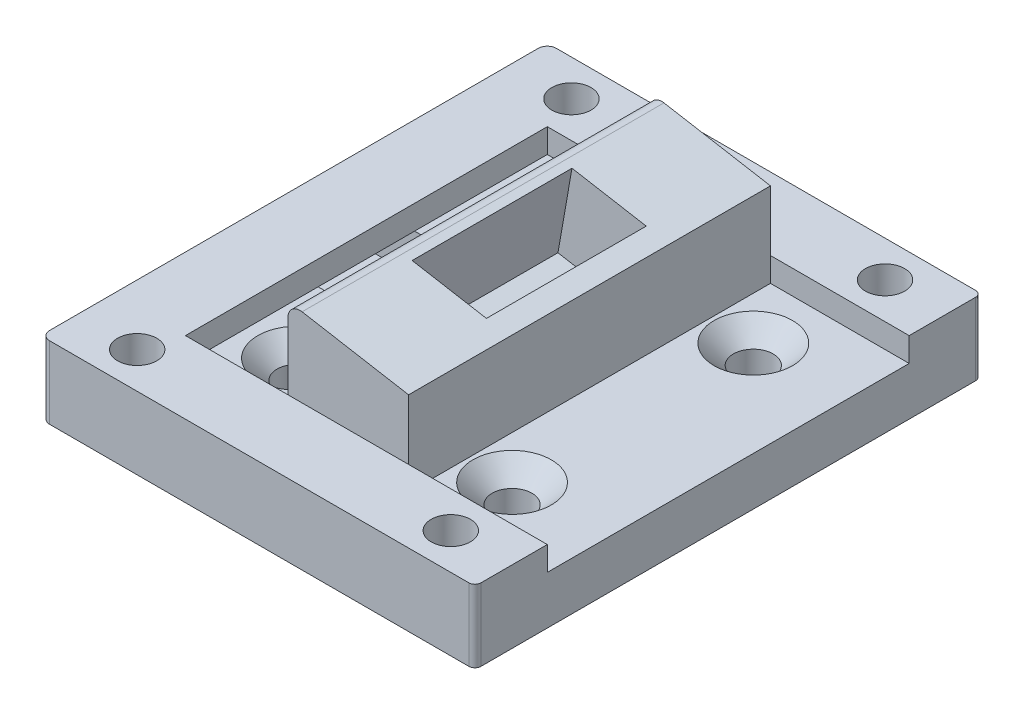
SolidWorks part; units mm, degrees
ref_plane "Ebene vorne" through (0, 0, 0) normal (0, 0, 1) x (1, 0, 0)
ref_plane "Ebene oben" through (0, 0, 0) normal (0, 1, 0) x (1, 0, 0)
ref_plane "Ebene rechts" through (0, 0, 0) normal (1, 0, 0) x (0, 0, -1)
sketch "Sketch1" plane through (0, 0, 0) normal (0, 1, 0) x (1, 0, 0)
  line L1 (15, -15) -> (-15, -15)
  line L2 (15, -15) -> (15, 15)
  line L3 (15, 15) -> (-15, 15)
  line L4 (-15, -15) -> (-15, 15)
  line L5 (15, -15) -> (-15, 15) construction
  line L6 (15, 15) -> (-15, -15) construction
  point P0 (0, 0)
  dimension "D1" = 30
  dimension "D2" = 30
extrude "Base Plate" add sketch "Sketch1" along normal blind 1.5
sketch "Sketch2" plane through (0, 0, 0) normal (0, -1, 0) x (1, 0, 0)
  line L1 (15, 15) -> (-15, 15)
  line L2 (15, 15) -> (15, 21)
  line L3 (15, 21) -> (-21, 21)
  line L5 (15, -15) -> (-15, -15)
  line L6 (15, -15) -> (15, -21)
  line L7 (15, -21) -> (-21, -21)
  line L11 (-15, -15) -> (-15, 15)
  line L13 (-21, -21) -> (-21, 21)
  dimension "D1" = 6
  dimension "D2" = 6
  dimension "D3" = 6
extrude "Side Walls" add sketch "Sketch2" against normal blind 6
sketch "Sketch3" plane through (0, 1.5, 0) normal (0, 1, 0) x (1, 0, 0)
  line L0 (15, 15) -> (-15, 15) construction
  line L1 (3.5, -15) -> (-6.5, -15)
  line L2 (3.5, -15) -> (3.5, 15)
  line L3 (3.5, 15) -> (-6.5, 15)
  line L4 (-6.5, -15) -> (-6.5, 15)
  line L5 (15, -15) -> (15, 15) construction
  dimension "D1" = 10
  dimension "D2" = 11.5
extrude "Switch Block" add sketch "Sketch3" along direction (0, -1, 0) on the side of the normal offset from surface (9.5 mm away) 5
sketch "Sketch11" plane through (0, 1.5, 0) normal (0, 1, 0) x (1, 0, 0)
  line L1 (-15, -15) -> (-6.5, -15)
  line L2 (-15, -15) -> (-15, 15)
  line L3 (-15, 15) -> (-6.5, 15)
  line L4 (-6.5, -15) -> (-6.5, 15)
  line L5 (3.5, 15) -> (15, 15)
  line L6 (3.5, 15) -> (3.5, -15)
  line L7 (3.5, -15) -> (15, -15)
  line L8 (15, 15) -> (15, -15)
extrude "Thicker Body" add sketch "Sketch11" along normal offset from surface (2.5 mm away) 4 up to face at (-3, 0, 0)
sketch "Sketch5" plane through (0, 0, -15) normal (0, 0, -1) x (-1, 0, 0)
  line L0 (6.5, 11) -> (6.5, 12.75)
  line L1 (6.5, 12.75) -> (-3.5, 11)
  line L2 (-3.5, 11) -> (6.5, 11)
  dimension "D1" = 1.75
extrude "Switch Block Angle" add sketch "Sketch5" against normal up to surface (30 mm away) up to face at (-1.5, 8.5, 15)
sketch "Sketch6" plane through (1.9718, 11.2674, 0) normal (0.1724, 0.985, 0) x (0.985, -0.1724, 0)
  line L0 (13.2262, 0) -> (10.2211, 0) construction
  line L1 (-6.6496, 6.625) -> (-0.3996, 6.625)
  line L2 (-6.6496, 6.625) -> (-6.6496, -6.625)
  line L3 (-6.6496, -6.625) -> (-0.3996, -6.625)
  line L4 (-0.3996, 6.625) -> (-0.3996, -6.625)
  line L5 (-6.6496, 6.625) -> (-0.3996, -6.625) construction
  line L6 (-6.6496, -6.625) -> (-0.3996, 6.625) construction
  line L7 (13.2262, 15) -> (13.2262, -15) construction
  line L8 (-3.5246, 15) -> (-3.5246, 4.9978) construction
  line L9 (-8.6005, 15) -> (1.5514, 15) construction
  point P0 (-3.5246, 0)
  dimension "D1" = 13.25
  dimension "D2" = 6.25
extrude "Switch Pocket" cut sketch "Sketch6" against normal blind 6.75
sketch "Sketch7" plane through (0.8082, 4.6185, 0) normal (0.1724, 0.985, 0) x (0.985, -0.1724, 0)
  line L0 (-6.6496, -6.625) -> (-0.3996, -6.625) construction
  line L1 (-4.8996, 6.625) -> (-2.1496, 6.625)
  line L2 (-4.8996, 6.625) -> (-4.8996, -6.625)
  line L3 (-4.8996, -6.625) -> (-2.1496, -6.625)
  line L4 (-2.1496, 6.625) -> (-2.1496, -6.625)
  line L5 (-4.8996, 6.625) -> (-2.1496, -6.625) construction
  line L6 (-4.8996, -6.625) -> (-2.1496, 6.625) construction
  line L7 (-6.6496, 0) -> (5.4128, 0) construction
  line L8 (-6.6496, 6.625) -> (-6.6496, -6.625) construction
  line L9 (-3.5246, -6.625) -> (-3.5246, -3.7808) construction
  line L10 (-3.5246, 6.625) -> (-3.5246, 0.9395) construction
  line L11 (-0.3996, 6.625) -> (-6.6496, 6.625) construction
  point P0 (-3.5246, 0)
  dimension "D1" = 2.75
extrude "Wire Channel 1" cut sketch "Sketch7" against normal offset from surface (4.0496 mm away) 1
sketch "Sketch19" plane through (0, 1, 0) normal (0, 1, 0) x (1, 0, 0)
  line L1 (-2.0072, -6.625) -> (-4.799, -6.625)
  line L2 (-2.0072, -6.625) -> (-2.0072, 6.625)
  line L3 (-2.0072, 6.625) -> (-4.799, 6.625)
  line L4 (-4.799, -6.625) -> (-4.799, 6.625)
extrude "Switch Remover" cut sketch "Sketch19" against normal blind 10
sketch "Sketch4" plane through (0, 6, 0) normal (0, 1, 0) x (1, 0, 0)
  line L0 (-21, -21) -> (-21, 21) construction
  line L2 (15, -15) -> (15, -21) construction
  line L3 (-15, 0) -> (-8.5625, 0) construction
  line L4 (-15, 15) -> (-15, -15) construction
  line L5 (15, -18) -> (1.31, -18) construction
  circle A0 centre (-16, -18) radius 1.625
  circle A1 centre (10, -18) radius 1.625
  circle A2 centre (10, 18) radius 1.625
  circle A3 centre (-16, 18) radius 1.625
  dimension "D1" = 3.25
  dimension "D2" = 5
  dimension "D5" = 5
extrude "M2 Screws" cut sketch "Sketch4" against normal up to surface (6 mm away) up to face at (-3.4031, 0, 0)
sketch "Sketch16" plane through (0, 0, 0) normal (0, -1, 0) x (1, 0, 0)
  line L0 (15, 0) -> (11.7077, 0) construction
  line L1 (-14.7731, 15.875) -> (-13.5463, 18)
  line L2 (-13.5463, 18) -> (-14.7731, 20.125)
  line L3 (-14.7731, 20.125) -> (-17.2269, 20.125)
  line L4 (-17.2269, 20.125) -> (-18.4537, 18)
  line L5 (-18.4537, 18) -> (-17.2269, 15.875)
  line L6 (-17.2269, 15.875) -> (-14.7731, 15.875)
  line L7 (15, 21) -> (15, -21) construction
  line L9 (15, 21) -> (-21, 21) construction
  line L10 (-17.2269, -15.875) -> (-14.7731, -15.875)
  line L11 (11.2269, 15.875) -> (12.4537, 18)
  line L12 (12.4537, 18) -> (11.2269, 20.125)
  line L13 (11.2269, 20.125) -> (8.7731, 20.125)
  line L14 (8.7731, 20.125) -> (7.5463, 18)
  line L15 (7.5463, 18) -> (8.7731, 15.875)
  line L16 (8.7731, 15.875) -> (11.2269, 15.875)
  line L17 (-18.4537, -18) -> (-17.2269, -15.875)
  line L18 (-17.2269, -20.125) -> (-18.4537, -18)
  line L19 (-14.7731, -20.125) -> (-17.2269, -20.125)
  line L20 (-13.5463, -18) -> (-14.7731, -20.125)
  line L21 (-14.7731, -15.875) -> (-13.5463, -18)
  line L22 (8.7731, -15.875) -> (11.2269, -15.875)
  line L23 (7.5463, -18) -> (8.7731, -15.875)
  line L24 (8.7731, -20.125) -> (7.5463, -18)
  line L25 (11.2269, -20.125) -> (8.7731, -20.125)
  line L26 (12.4537, -18) -> (11.2269, -20.125)
  line L27 (11.2269, -15.875) -> (12.4537, -18)
  circle A0 centre (-16, 18) radius 2.125 construction
  circle A1 centre (10, 18) radius 2.125 construction
  circle A2 centre (-16, -18) radius 2.125 construction
  circle A3 centre (10, -18) radius 2.125 construction
  dimension "D1" = 4.25
extrude "M2 Nuts" cut sketch "Sketch16" against normal blind 2
sketch "Sketch17" plane through (0, 4, 0) normal (0, 1, 0) x (1, 0, 0)
  line L0 (0, 0) -> (7.0789, 0) construction
  line L1 (-10.75, -15) -> (-10.75, -13.4401) construction
  line L2 (-15, -15) -> (-6.5, -15) construction
  circle A0 centre (7.0789, 10) radius 1.65
  circle A1 centre (7.0789, -10) radius 1.65
  circle A2 centre (-10.75, -10) radius 1.65
  circle A3 centre (-10.75, 10) radius 1.65
  dimension "D1" = 3.3
  dimension "D2" = 10
  dimension "D3" = 20
extrude "M3 Mounting Screws" cut sketch "Sketch17" against normal through all
sketch "Sketch18" plane through (0, 4, 0) normal (0, 1, 0) x (1, 0, 0)
  circle A0 centre (7.0789, 10) radius 3.25
  circle A1 centre (7.0789, -10) radius 3.25
  circle A2 centre (-10.75, -10) radius 3.25
  circle A3 centre (-10.75, 10) radius 3.25
  dimension "D1" = 6.5
extrude "M3 Heads" cut sketch "Sketch18" against normal blind 10 draft 45
ref_plane "Plane1" through (-4.018, 0, 0) normal (-1, 0, 0) x (0, 0, 1)
sketch "Sketch8" plane through (-4.018, 2.0997, 0) normal (-1, 0, 0) x (0, 0, 1)
  line L0 (-6.625, -2.0997) -> (6.625, -2.0997) construction
  line L1 (-4, -1.3497) -> (4, -1.3497)
  line L2 (-4, -1.3497) -> (-4, 1.9003)
  line L3 (-4, 1.9003) -> (4, 1.9003)
  line L4 (4, -1.3497) -> (4, 1.9003)
  line L5 (-4, -1.3497) -> (4, 1.9003) construction
  line L6 (-4, 1.9003) -> (4, -1.3497) construction
  line L7 (0, -2.0997) -> (0, 1.6764) construction
  line L8 (15, 1.9003) -> (-15, 1.9003) construction
  line L9 (-6.625, -2.0997) -> (6.625, -2.0997) construction
  point P0 (0, 0.2753)
  dimension "D1" = 0.75
  dimension "D2" = 8
extrude "Wire Channel" cut sketch "Sketch8" along normal up to surface (16.982 mm away) up to face at (-21, 3, 0)
fillet "Fillet1" radius 1 1 edges at (-6.5, 12.75, 0)
fillet "Fillet2" radius 0.5 1 edges at (15, 3, 21)
fillet "Fillet3" radius 0.5 1 edges at (15, 3, -21)
fillet "Fillet4" radius 0.75 1 edges at (-21, 3, -21)
fillet "Fillet5" radius 0.75 1 edges at (-21, 3, 21)
